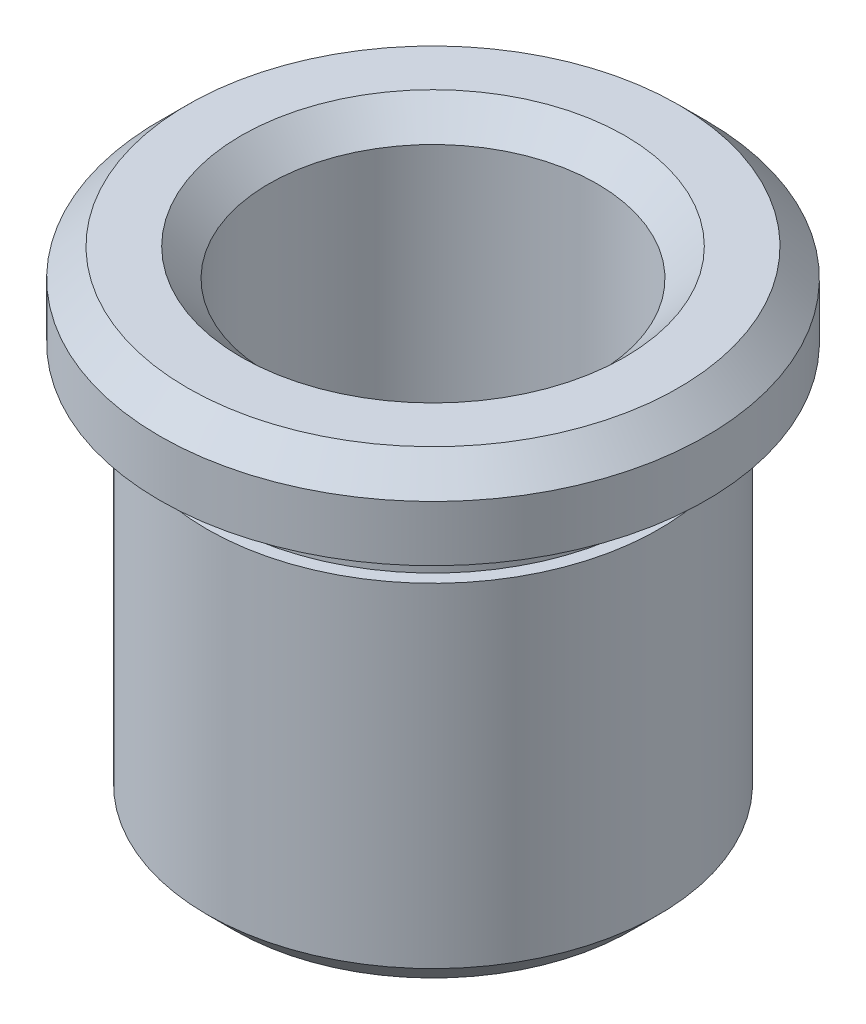
SolidWorks part; units mm, degrees
ref_plane "Front Plane" through (0, 0, 0) normal (0, 0, 1) x (1, 0, 0)
ref_plane "Top Plane" through (0, 0, 0) normal (0, 1, 0) x (1, 0, 0)
ref_plane "Right Plane" through (0, 0, 0) normal (1, 0, 0) x (0, 0, -1)
sketch "Sketch1" plane through (0, 0, 0) normal (0, 0, 1) x (1, 0, 0)
  line L0 (1.4224, 0) -> (3.6195, 0)
  line L1 (3.6195, 0) -> (4.1275, 0.508)
  line L2 (4.1275, 0.508) -> (4.1275, 6.604)
  line L3 (4.1275, 6.604) -> (3.8989, 6.604)
  line L4 (3.8989, 6.604) -> (3.8989, 7.493)
  line L5 (3.8989, 7.493) -> (4.9911, 7.493)
  line L6 (4.9911, 7.493) -> (4.9911, 8.509)
  line L7 (4.9911, 8.509) -> (4.4831, 9.017)
  line L8 (4.4831, 9.017) -> (3.5052, 9.017)
  line L9 (2.9972, 8.509) -> (2.9972, 2.1345)
  line L10 (2.9972, 2.1345) -> (2.1975, 1.3348)
  line L11 (2.1975, 1.3348) -> (1.4224, 1.3348)
  line L12 (1.4224, 1.3348) -> (1.4224, 0)
  line L13 (1.4224, 0) -> (0, 0) construction
  line L14 (0, 0) -> (0, 9.017) construction
  line L15 (0, 9.017) -> (2.9972, 9.017) construction
  line L16 (3.5052, 9.017) -> (2.9972, 8.509)
  dimension "D1" = 9.017
  dimension "D2" = 2.8448
  dimension "D3" = 7.7978
  dimension "D4" = 1.524
  dimension "D5" = 0.889
  dimension "D6" = 45
  dimension "D7" = 45
  dimension "D8" = 8.255
  dimension "D9" = 9.9822
  dimension "D10" = 0.508
  dimension "D11" = 0.508
  dimension "D12" = 5.9944
revolve "Revolve1" add sketch "Sketch1" angle 360 about L14
